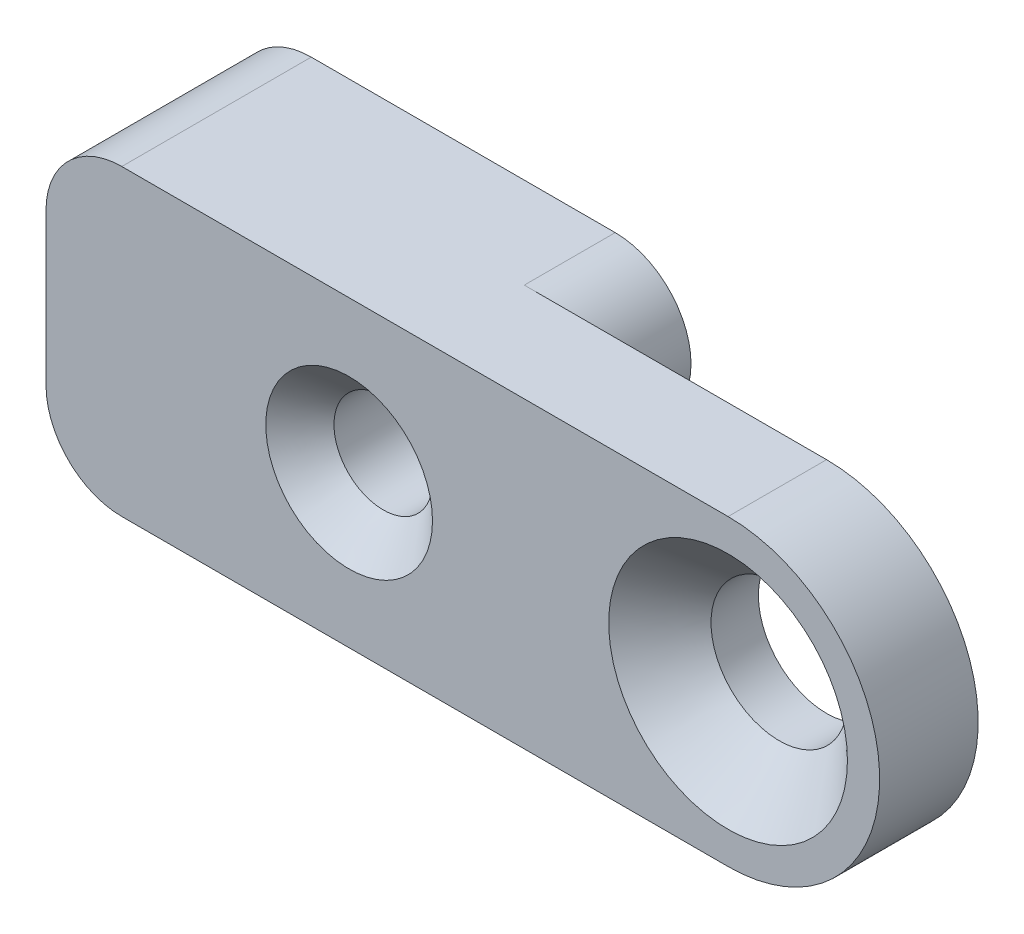
SolidWorks part; units mm, degrees
material "ABS"
ref_plane "Front Plane" through (0, 0, 0) normal (0, 0, 1) x (1, 0, 0)
ref_plane "Top Plane" through (0, 0, 0) normal (0, 1, 0) x (1, 0, 0)
ref_plane "Right Plane" through (0, 0, 0) normal (1, 0, 0) x (0, 0, -1)
sketch "Sketch1" plane through (0, 0, 0) normal (0, 0, 1) x (1, 0, 0)
  line L0 (10, 4) -> (-8, 4)
  line L1 (10, -4) -> (-8, -4)
  line L2 (-15, 3.5) -> (0, 2) construction
  line L3 (-15, -3.5) -> (0, -2) construction
  line L4 (-8, 4) -> (-8, 3.011)
  line L5 (-8, 3.011) -> (0.2189, 2.1891)
  line L6 (-8, -4) -> (-8, -3.011)
  line L7 (-8, -3.011) -> (0.2189, -2.1891)
  line L8 (-15, 0) -> (10, 0) construction
  circle A1 centre (10, 0) radius 1.725
  arc A2 (10, -4) -> (10, 4) centre (10, 0) ccw
  arc A3 (0.2189, 2.1891) -> (0.2189, -2.1891) centre (0, 0) cw
  arc A4 (-14.3069, 3.4307) -> (-14.3069, -3.4307) centre (-15, 0) ccw construction
  arc A5 (0, -2) -> (0, 2) centre (0, 0) ccw construction
  dimension "D1" = 2
  dimension "D2" = 3.45
  dimension "D4" = 2.2
  dimension "D5" = 3.5
  dimension "D9" = 4
  dimension "D3" = 25
  dimension "D7" = 15
  dimension "D8" = 18
extrude "Boss-Extrude1" add sketch "Sketch1" along normal blind 2
sketch "Sketch2" plane through (0, 0, 2) normal (0, 0, 1) x (1, 0, 0)
  line L0 (-8, 4) -> (-8, -4)
  line L1 (10, 4) -> (-8, 4) construction
  line L2 (-8, -4) -> (10, -4) construction
  line L3 (10, 4) -> (-8, 4)
  line L4 (-8, -4) -> (10, -4)
  arc A0 (10, -4) -> (10, 4) centre (10, 0) ccw construction
  arc A1 (10, -4) -> (10, 4) centre (10, 0) ccw
  circle A2 centre (0, 0) radius 1
  circle A3 centre (10, 0) radius 1.725 construction
  circle A4 centre (10, 0) radius 1.725
  dimension "D1" = 2
extrude "Boss-Extrude2" add sketch "Sketch2" along normal blind 3
sketch "Sketch3" plane through (0, 0, 0) normal (0, 0, -1) x (-1, 0, 0)
  circle A0 centre (-10, 0) radius 6.225
  dimension "D1" = 12.45
extrude "Cut-Extrude1" cut sketch "Sketch3" against normal blind 2.4
hole_wizard "CSK for M3 Flat Head Machine Screw2" positions "3DSketch4" profile "Sketch6" countersink size "M3" standard "ANSI Metric" end condition through all
sketch3d "3DSketch4"
  circle A0 centre (10, 0, 5) radius 1.725 construction
  point P0 (10, 0, 5)
  point P8 (10, 0, 6.725)
sketch "Sketch6" plane through (10, 0, 5) normal (1, 0, 0) x (0, -1, 0)
  line L0 (0, 0) -> (0, 5)
  line L1 (0, 5) -> (1.8, 5)
  line L2 (1.8, 5) -> (1.8, 1.35)
  line L3 (1.8, 1.35) -> (3.15, 0)
  line L5 (3.15, 0) -> (0, 0)
  line L6 (-1.8, 1.35) -> (-3.15, 0) construction
  line L11 (0, -6.35) -> (0, 107.95) construction
  dimension "Thru Hole Dia." = 3.6
  dimension "Thru Hole Depth" = 5
  dimension "Near C'Sink Dia." = 6.3
  dimension "Near C'Sink Angle" = 90
hole_wizard "CSK for M2 Flat Head Machine Screw1" positions "3DSketch5" profile "Sketch7" countersink size "M2" standard "ANSI Metric" end condition through all
sketch3d "3DSketch5"
  circle A0 centre (0, 0, 5) radius 1 construction
  point P0 (0, 0, 5)
  point P6 (0, 0, 6)
sketch "Sketch7" plane through (0, 0, 5) normal (1, 0, 0) x (0, -1, 0)
  line L0 (0, 0) -> (0, 5)
  line L1 (0, 5) -> (1.3, 5)
  line L2 (1.3, 5) -> (1.3, 0.9)
  line L3 (1.3, 0.9) -> (2.2, 0)
  line L5 (2.2, 0) -> (0, 0)
  line L6 (-1.3, 0.9) -> (-2.2, 0) construction
  line L11 (0, -6.35) -> (0, 107.95) construction
  dimension "Thru Hole Dia." = 2.6
  dimension "Thru Hole Depth" = 5
  dimension "Near C'Sink Dia." = 4.4
  dimension "Near C'Sink Angle" = 90
fillet "Fillet1" radius 2 4 edges at (5.2302, 4, 1.2) (5.2302, -4, 1.2) (-8, -4, 2.5) (-8, 4, 2.5)
equation "\"D1@Sketch3\"=12+\"print_free@Parameters@FabricationParameters.sldprt\""
equation "\"D4@Sketch1\"=2+\"print_fit@Parameters@FabricationParameters.sldprt\""
equation "\"D2@Sketch1\"=3+\"print_free@Parameters@FabricationParameters.sldprt\""
